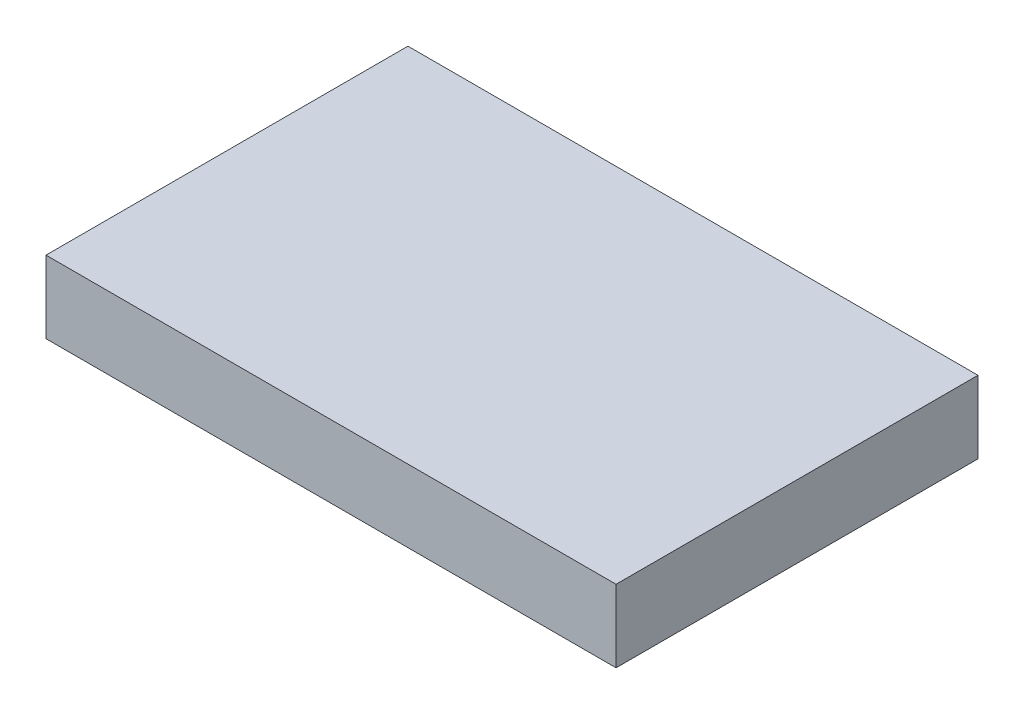
SolidWorks part; units mm, degrees
material "Beech"
ref_plane "Front Plane" through (0, 0, 0) normal (0, 0, 1) x (1, 0, 0)
ref_plane "Top Plane" through (0, 0, 0) normal (0, 1, 0) x (1, 0, 0)
ref_plane "Right Plane" through (0, 0, 0) normal (1, 0, 0) x (0, 0, -1)
sketch "Sketch1" plane through (0, 0, 0) normal (0, 1, 0) x (1, 0, 0)
  line L1 (0, 0) -> (304.8, 0)
  line L2 (0, 0) -> (0, 304.8)
  line L3 (0, 304.8) -> (304.8, 304.8)
  line L4 (304.8, 0) -> (304.8, 304.8)
  dimension "D1" = 304.8
  dimension "D2" = 304.8
extrude "Boss-Extrude1" add sketch "Sketch1" along normal blind 6.35
sketch "Sketch2" plane through (0, 6.35, 0) normal (0, 1, 0) x (1, 0, 0)
  line L1 (304.8, 304.8) -> (0, 304.8) construction
  line L2 (50.0062, 304.8) -> (50.0062, 273.05)
  line L3 (50.0062, 273.05) -> (0, 273.05)
  line L4 (0, 304.8) -> (0, 0) construction
  line L6 (0, 273.05) -> (0, 0)
  line L7 (0, 0) -> (304.8, 0)
  line L8 (304.8, 0) -> (304.8, 304.8)
  line L9 (304.8, 304.8) -> (50.0062, 304.8)
  dimension "D1" = 50.0062
  dimension "D2" = 31.75
extrude "Cut-Extrude2" cut sketch "Sketch2" against normal blind 6.35 contours L3 L6 L7 L8 L9 L2
